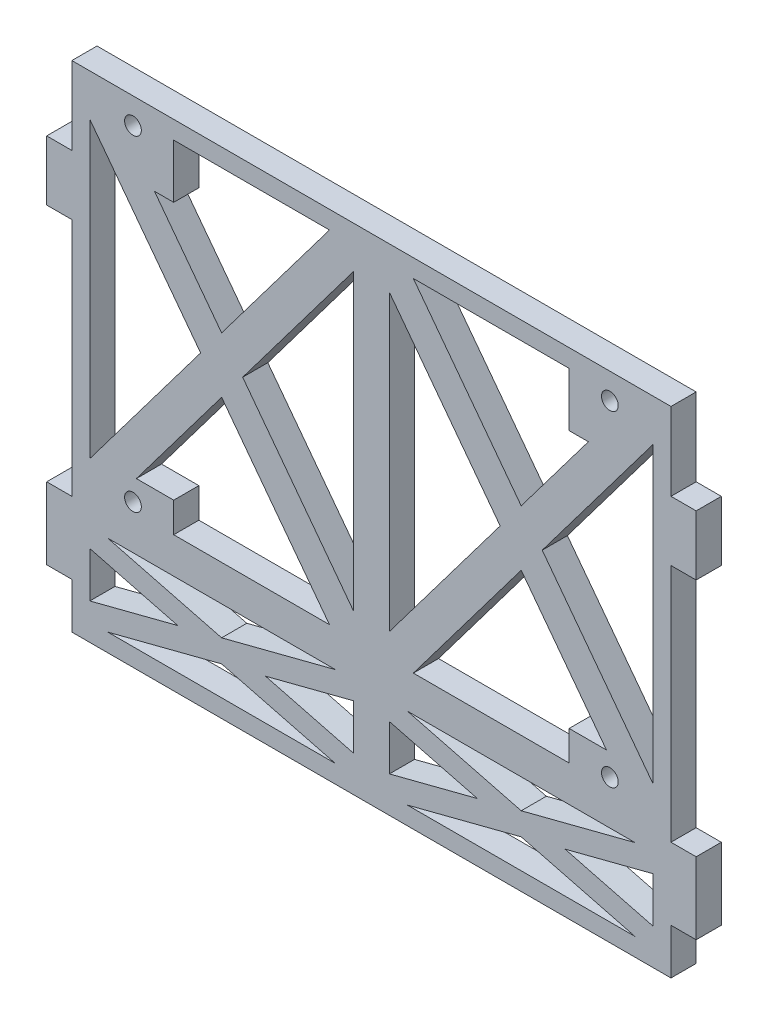
SolidWorks part; units mm, degrees
ref_plane "Front Plane" through (0, 0, 0) normal (0, 0, 1) x (1, 0, 0)
ref_plane "Top Plane" through (0, 0, 0) normal (0, 1, 0) x (1, 0, 0)
ref_plane "Right Plane" through (0, 0, 0) normal (1, 0, 0) x (0, 0, -1)
sketch "Sketch1" plane through (0, 0, 0) normal (0, 0, 1) x (1, 0, 0)
  line L1 (-63.5, 40) -> (63.5, 40)
  line L2 (-63.5, 40) -> (-63.5, -40)
  line L3 (-63.5, -40) -> (63.5, -40)
  line L4 (63.5, 40) -> (63.5, -40)
  line L5 (-63.5, 40) -> (63.5, -40) construction
  line L6 (-63.5, -40) -> (63.5, 40) construction
  point P0 (0, 0)
  dimension "D1" = 127
  dimension "D2" = 80
extrude "Top" add sketch "Sketch1" against normal blind 5.334
sketch "Sketch2" plane through (0, -40, 0) normal (0, -1, 0) x (1, 0, 0)
  line L1 (-63.5, 0) -> (63.5, 0)
  line L2 (-63.5, 0) -> (-63.5, -5.334)
  line L3 (-63.5, -5.334) -> (63.5, -5.334)
  line L4 (63.5, 0) -> (63.5, -5.334)
extrude "Bottom" add sketch "Sketch2" along normal blind 24.9234
sketch "Sketch4" plane through (63.5, 0, 0) normal (1, 0, 0) x (0, 0, -1)
  line L1 (0, -64.9234) -> (0, 40) construction
  line L2 (0, -40) -> (5.334, -40)
  line L3 (0, -40) -> (0, -55.24)
  line L4 (0, -55.24) -> (5.334, -55.24)
  line L5 (5.334, -40) -> (5.334, -55.24)
  line L6 (5.334, -64.9234) -> (5.334, 40) construction
  line L7 (0, 23.5) -> (5.334, 23.5)
  line L8 (0, 23.5) -> (0, 10.8)
  line L9 (0, 10.8) -> (5.334, 10.8)
  line L10 (5.334, 23.5) -> (5.334, 10.8)
  dimension "D1" = 50.8
  dimension "D2" = 24.9234
  dimension "D3" = 15.24
  dimension "D4" = 12.7
extrude "RightTooth" add sketch "Sketch4" along normal blind 5.334
sketch "Sketch5" plane through (-63.5, 0, 0) normal (-1, 0, 0) x (0, 0, 1)
  line L0 (-5.334, 40) -> (-5.334, -64.9234) construction
  line L1 (-5.334, -40) -> (0, -40)
  line L2 (-5.334, -40) -> (-5.334, -55.24)
  line L3 (-5.334, -55.24) -> (0, -55.24)
  line L4 (0, -40) -> (0, -55.24)
  line L5 (0, 40) -> (0, -64.9234) construction
  line L7 (-5.334, 23.5) -> (0, 23.5)
  line L8 (-5.334, 23.5) -> (-5.334, 10.8)
  line L9 (-5.334, 10.8) -> (0, 10.8)
  line L10 (0, 23.5) -> (0, 10.8)
  dimension "D1" = 24.9234
  dimension "D2" = 15.24
  dimension "D3" = 50.8
  dimension "D4" = 12.7
extrude "LeftTooth" add sketch "Sketch5" along normal blind 5.334
sketch "Sketch6" plane through (0, 0, 0) normal (0, 0, 1) x (1, 0, 0)
  line L0 (0, 0) -> (-50000, 0) construction
  line L1 (0, 0) -> (0, 50000) construction
  line L3 (-55, 40) -> (55, 40) construction
  line L4 (-55, 40) -> (-55, -40) construction
  line L5 (-55, -40) -> (55, -40) construction
  line L6 (55, 40) -> (55, -40) construction
  line L7 (-55, 40) -> (55, -40) construction
  line L8 (-55, -40) -> (55, 40) construction
  circle A0 centre (-50.546, 34.544) radius 1.775
  circle A1 centre (50.546, 34.544) radius 1.775
  circle A2 centre (50.546, -34.544) radius 1.775
  circle A3 centre (-50.546, -34.544) radius 1.775
  point P5 (0, 0)
  dimension "D3" = 3.55
  dimension "D1" = 110
  dimension "D2" = 80
  dimension "D4" = 50.546
  dimension "D5" = 34.544
extrude "PerfBoardScrewCuts" cut sketch "Sketch6" against normal through all
sketch "Sketch7" plane through (0, 0, 0) normal (0, 0, 1) x (1, 0, 0)
  line L0 (0, -40.0651) -> (0, -64.9234) construction
  line L1 (63.5, -64.9234) -> (-63.5, -64.9234) construction
  line L2 (63.5, -40.0651) -> (-63.5, -40.0651) construction
  line L3 (-63.5, 40) -> (-63.5, 23.5) construction
  line L4 (-59.69, -47.6851) -> (-7.62, -61.1134)
  line L5 (-59.69, -43.8751) -> (-3.81, -43.8751)
  line L6 (-59.69, -43.8751) -> (-59.69, -61.1134)
  line L7 (-59.69, -61.1134) -> (-3.81, -61.1134)
  line L8 (-3.81, -43.8751) -> (-3.81, -61.1134)
  line L9 (-59.69, -43.8751) -> (-3.81, -61.1134) construction
  line L10 (-59.69, -61.1134) -> (-3.81, -43.8751) construction
  line L11 (-55.88, -43.8751) -> (-3.81, -57.3034)
  line L12 (-55.88, -61.1134) -> (-3.81, -47.6851)
  line L13 (-7.62, -43.8751) -> (-59.69, -57.3034)
  line L14 (0, -40.0651) -> (0, 40) construction
  line L15 (63.5, 40) -> (-63.5, 40) construction
  line L16 (-63.5, -36.2551) -> (63.5, -36.2551) construction
  line L17 (-3.81, -36.2551) -> (-3.81, 40) construction
  line L18 (-59.69, -36.2551) -> (-59.69, 40) construction
  line L19 (-59.69, 36.19) -> (-3.81, 36.19) construction
  line L20 (-54.61, 36.19) -> (-3.81, -31.1751)
  line L21 (-8.89, -36.2551) -> (-59.69, 31.11)
  line L22 (-59.69, -31.1751) -> (-8.89, 36.19)
  line L23 (-54.61, -36.2551) -> (-3.81, 31.11)
  line L24 (-59.69, 36.19) -> (-3.81, 36.19)
  line L25 (-59.69, 36.19) -> (-59.69, -36.2551)
  line L26 (-59.69, -36.2551) -> (-3.81, -36.2551)
  line L27 (-3.81, -36.2551) -> (-3.81, 36.19)
  line L28 (59.69, 36.19) -> (3.81, 36.19) construction
  line L29 (59.69, -36.2551) -> (59.69, 40) construction
  line L30 (3.81, -36.2551) -> (3.81, 40) construction
  line L31 (59.69, -61.1134) -> (3.81, -43.8751) construction
  line L32 (59.69, -43.8751) -> (3.81, -61.1134) construction
  line L33 (41.91, 24.76) -> (41.91, 36.19)
  line L34 (45.9906, 24.76) -> (41.91, 24.76)
  line L35 (41.91, -29.9051) -> (41.91, -36.2551)
  line L36 (49.8215, -29.9051) -> (41.91, -29.9051)
  line L37 (3.81, -36.2551) -> (3.81, 36.19)
  line L38 (59.69, -36.2551) -> (3.81, -36.2551)
  line L39 (59.69, 36.19) -> (59.69, -36.2551)
  line L40 (59.69, 36.19) -> (3.81, 36.19)
  line L41 (54.61, -36.2551) -> (3.81, 31.11)
  line L42 (59.69, -31.1751) -> (8.89, 36.19)
  line L43 (8.89, -36.2551) -> (59.69, 31.11)
  line L44 (54.61, 36.19) -> (3.81, -31.1751)
  line L45 (7.62, -43.8751) -> (59.69, -57.3034)
  line L46 (55.88, -61.1134) -> (3.81, -47.6851)
  line L47 (55.88, -43.8751) -> (3.81, -57.3034)
  line L48 (3.81, -43.8751) -> (3.81, -61.1134)
  line L49 (-49.8215, -29.9051) -> (-41.91, -29.9051)
  line L50 (-41.91, -29.9051) -> (-41.91, -36.2551)
  line L51 (-45.9906, 24.76) -> (-41.91, 24.76)
  line L52 (-41.91, 24.76) -> (-41.91, 36.19)
  line L53 (59.69, -61.1134) -> (3.81, -61.1134)
  line L54 (59.69, -43.8751) -> (59.69, -61.1134)
  line L55 (59.69, -43.8751) -> (3.81, -43.8751)
  line L56 (59.69, -47.6851) -> (7.62, -61.1134)
  point P9 (-31.75, -52.4942)
  point P50 (0, -36.2551)
  point P81 (31.75, -52.4942)
  dimension "D1" = 3.81
  dimension "D2" = 3.81
  dimension "D3" = 3.81
  dimension "D4" = 3.81
  dimension "D5" = 3.81
  dimension "D6" = 3.81
  dimension "D7" = 3.81
  dimension "D8" = 3.81
  dimension "D9" = 3.81
  dimension "D10" = 3.81
  dimension "D11" = 3.81
  dimension "D12" = 3.81
  dimension "D13" = 3.81
  dimension "D14" = 3.81
  dimension "D15" = 5.08
  dimension "D16" = 5.08
  dimension "D17" = 5.08
  dimension "D18" = 5.08
  dimension "D19" = 5.08
  dimension "D20" = 5.08
  dimension "D21" = 5.08
  dimension "D22" = 5.08
  dimension "D23" = 6.35
  dimension "D24" = 12.7
  dimension "D25" = 12.7
  dimension "D26" = 6.35
extrude "Design" cut sketch "Sketch7" against normal blind 5.334 contours L21 L25 L22 | L52 L51 L20 L22 L24 | L49 L50 L26 L21 L23 | L20 L27 L23 | L44 L41 L37 | L44 L34 L33 L40 L42 | L43 L42 L39 | L43 L38 L35 L36 L41 | L47 L55 L45 | L54 L56 L45 | L46 L56 L53 | L46 L48 L47 | L12 L11 L8 | L13 L5 L11 | L13 L4 L6 | L12 L7 L4
